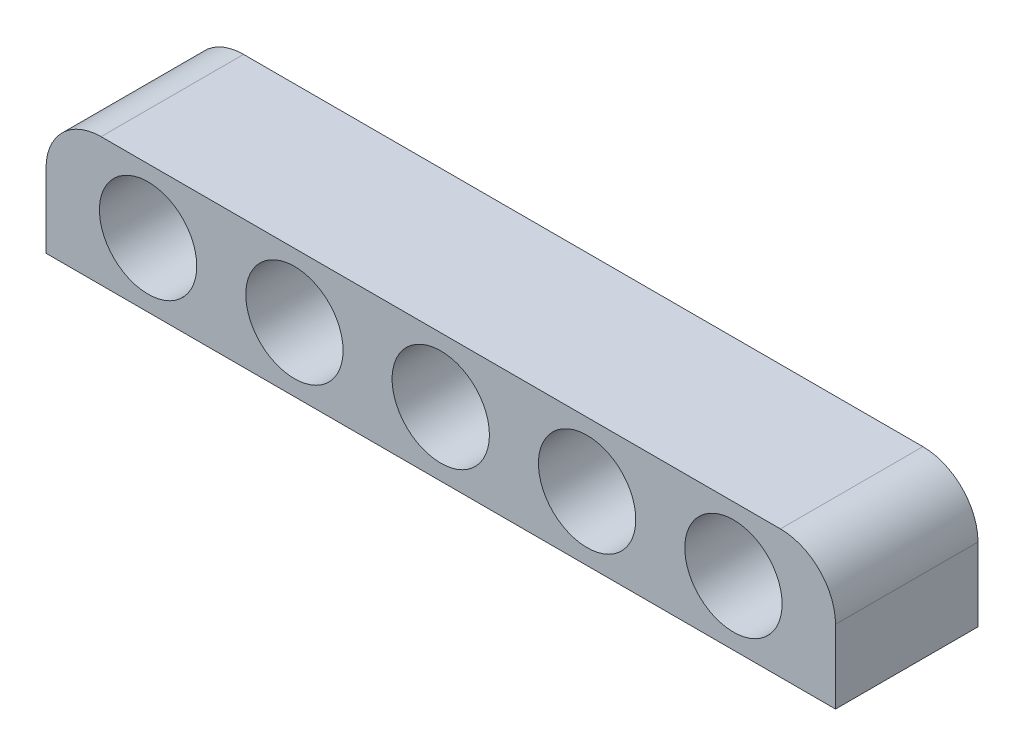
SolidWorks part; units mm, degrees
ref_plane "Front Plane" through (0, 0, 0) normal (0, 0, 1) x (1, 0, 0)
ref_plane "Top Plane" through (0, 0, 0) normal (0, 1, 0) x (1, 0, 0)
ref_plane "Right Plane" through (0, 0, 0) normal (1, 0, 0) x (0, 0, -1)
sketch "Sketch1" plane through (0, 0, 0) normal (0, 0, 1) x (1, 0, 0)
  line L1 (-15, 3) -> (15, 3)
  line L2 (-15, 3) -> (-15, -3)
  line L3 (-15, -3) -> (15, -3)
  line L4 (15, 3) -> (15, -3)
  line L5 (-15, 3) -> (15, -3) construction
  line L6 (-15, -3) -> (15, 3) construction
  point P0 (0, 0)
  dimension "D1" = 6
  dimension "D2" = 30
extrude "Boss-Extrude1" add sketch "Sketch1" along normal blind 7.76
sketch "Sketch2" plane through (0, 0, 7.76) normal (0, 0, 1) x (1, 0, 0)
  circle A0 centre (0, 0) radius 2.65
  circle A1 centre (7.97, 0) radius 2.65
  circle A2 centre (-7.97, 0) radius 2.65
  dimension "D1" = 5.3
  dimension "D2" = 5.3
  dimension "D4" = 5.3
  dimension "D3" = 7.97
  dimension "D5" = 7.97
extrude "Cut-Extrude1" cut sketch "Sketch2" against normal blind 8
sketch "Sketch3" plane through (-15, 0, 0) normal (-1, 0, 0) x (0, 0, 1)
  line L1 (0, 3) -> (7.76, 3)
  line L2 (0, 3) -> (0, -3)
  line L3 (0, -3) -> (7.76, -3)
  line L4 (7.76, 3) -> (7.76, -3)
extrude "Boss-Extrude2" add sketch "Sketch3" along normal blind 6
sketch "Sketch4" plane through (15, 0, 0) normal (1, 0, 0) x (0, 0, -1)
  line L1 (-7.76, 3) -> (0, 3)
  line L2 (-7.76, 3) -> (-7.76, -3)
  line L3 (-7.76, -3) -> (0, -3)
  line L4 (0, 3) -> (0, -3)
extrude "Boss-Extrude3" add sketch "Sketch4" along normal blind 6
sketch "Sketch5" plane through (0, 0, 7.76) normal (0, 0, 1) x (1, 0, 0)
  circle A0 centre (-15.94, 0) radius 2.65
  circle A1 centre (15.94, 0) radius 2.65
  circle A2 centre (-7.97, 0) radius 2.65 construction
  circle A3 centre (7.97, 0) radius 2.65 construction
  dimension "D1" = 5.3
  dimension "D2" = 5.3
  dimension "D3" = 7.97
  dimension "D4" = 7.97
extrude "Cut-Extrude2" cut sketch "Sketch5" against normal blind 8
sketch "Sketch6" plane through (0, 3, 0) normal (0, 1, 0) x (1, 0, 0)
  line L1 (-21, 0) -> (21, 0)
  line L2 (-21, 0) -> (-21, -7.76)
  line L3 (-21, -7.76) -> (21, -7.76)
  line L4 (21, 0) -> (21, -7.76)
extrude "Boss-Extrude4" add sketch "Sketch6" along normal blind 0.5
sketch "Sketch7" plane through (21, 0, 0) normal (1, 0, 0) x (0, 0, -1)
  line L1 (-7.76, 3.5) -> (0, 3.5)
  line L2 (-7.76, 3.5) -> (-7.76, -3)
  line L3 (-7.76, -3) -> (0, -3)
  line L4 (0, 3.5) -> (0, -3)
extrude "Boss-Extrude5" add sketch "Sketch7" along normal blind 0.5
sketch "Sketch8" plane through (0, -3, 0) normal (0, -1, 0) x (1, 0, 0)
  line L1 (-21, 7.76) -> (21.5, 7.76)
  line L2 (-21, 7.76) -> (-21, 0)
  line L3 (-21, 0) -> (21.5, 0)
  line L4 (21.5, 7.76) -> (21.5, 0)
extrude "Boss-Extrude6" add sketch "Sketch8" along normal blind 0.5
sketch "Sketch9" plane through (-21, 0, 0) normal (-1, 0, 0) x (0, 0, 1)
  line L1 (0, 3.5) -> (7.76, 3.5)
  line L2 (0, 3.5) -> (0, -3.5)
  line L3 (0, -3.5) -> (7.76, -3.5)
  line L4 (7.76, 3.5) -> (7.76, -3.5)
extrude "Boss-Extrude7" add sketch "Sketch9" along normal blind 0.5
fillet "Fillet1" radius 3 2 edges at (-21.5, 3.5, 3.88) (21.5, 3.5, 3.88)
